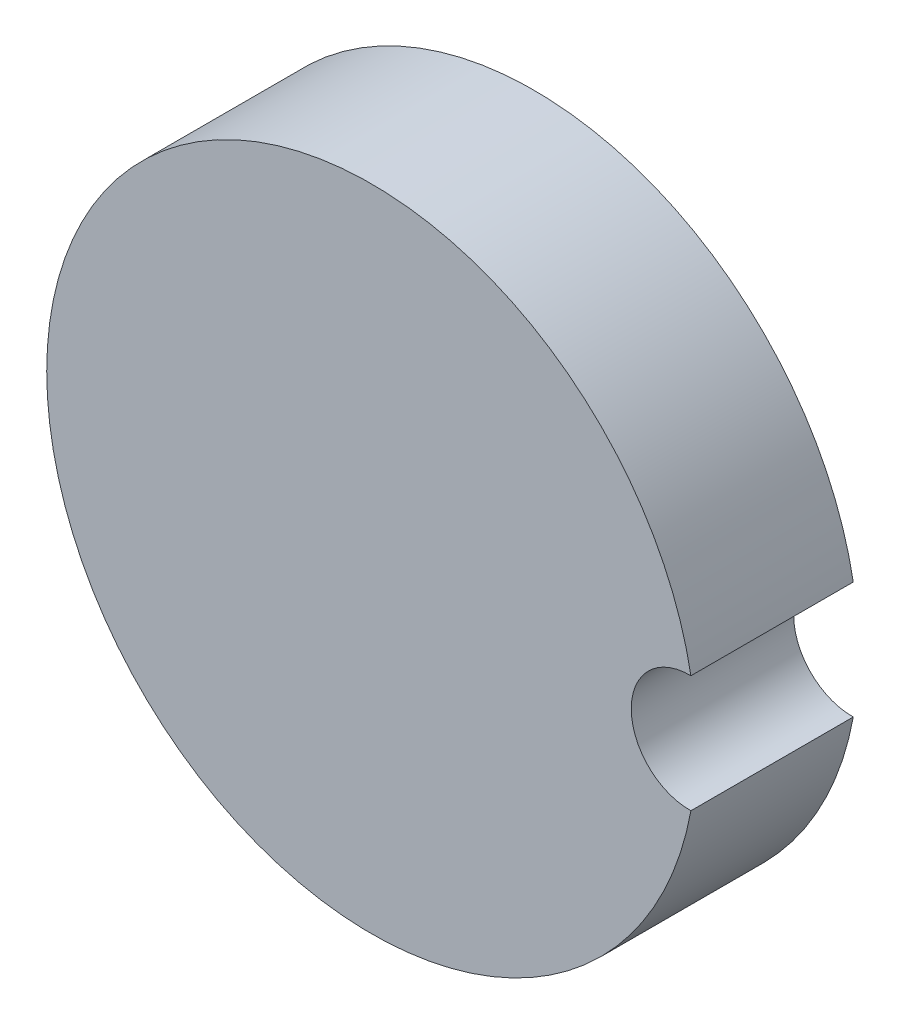
SolidWorks part; units mm, degrees
ref_plane "Front Plane" through (0, 0, 0) normal (0, 0, 1) x (1, 0, 0)
ref_plane "Top Plane" through (0, 0, 0) normal (0, 1, 0) x (1, 0, 0)
ref_plane "Right Plane" through (0, 0, 0) normal (1, 0, 0) x (0, 0, -1)
sketch "Sketch1" plane through (0, 0, 0) normal (0, 0, 1) x (1, 0, 0)
  circle A0 centre (0, 0) radius 100
extrude "Boss-Extrude1" add sketch "Sketch1" along normal blind 50
sketch "Sketch2" plane through (0, 0, 50) normal (0, 0, 1) x (1, 0, 0)
  circle A0 centre (98, 0) radius 18
extrude "Cut-Extrude1" cut sketch "Sketch2" against normal blind 50
